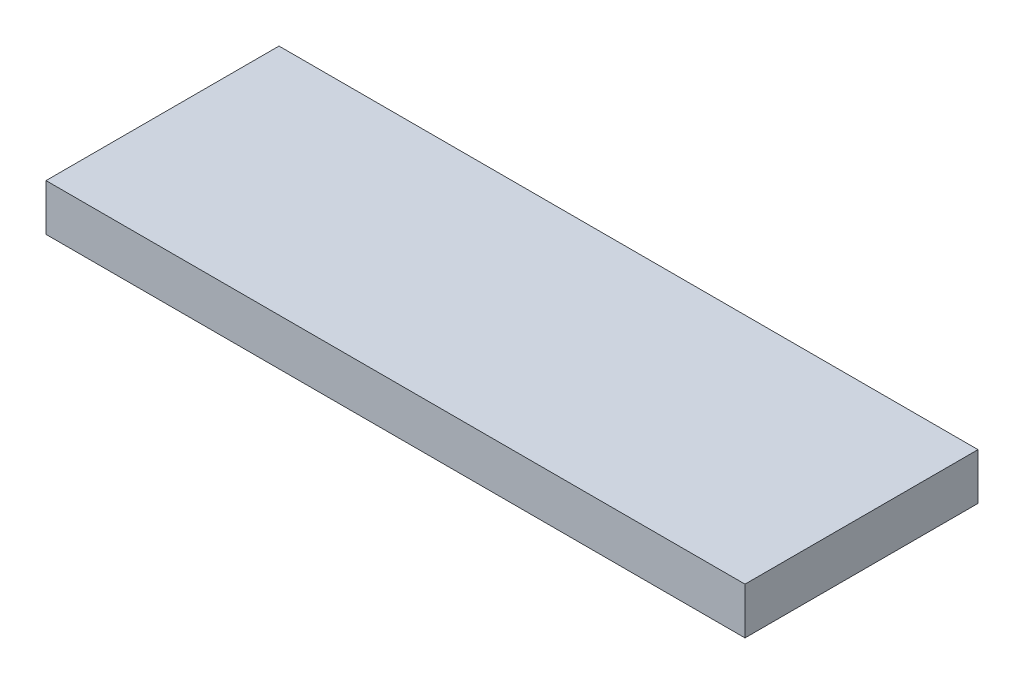
SolidWorks part; units mm, degrees
material "Copper"
ref_plane "Front Plane" through (0, 0, 0) normal (0, 0, 1) x (1, 0, 0)
ref_plane "Top Plane" through (0, 0, 0) normal (0, 1, 0) x (1, 0, 0)
ref_plane "Right Plane" through (0, 0, 0) normal (1, 0, 0) x (0, 0, -1)
sketch "Sketch1" plane through (0, 0, 0) normal (0, 1, 0) x (1, 0, 0)
  line L1 (0, 0) -> (38.1, 0)
  line L2 (0, 0) -> (0, 12.7)
  line L3 (0, 12.7) -> (38.1, 12.7)
  line L4 (38.1, 0) -> (38.1, 12.7)
  dimension "D1" = 38.1
  dimension "D2" = 12.7
extrude "Boss-Extrude1" add sketch "Sketch1" along normal blind 2.54 contours L2 L3 L4 L1
